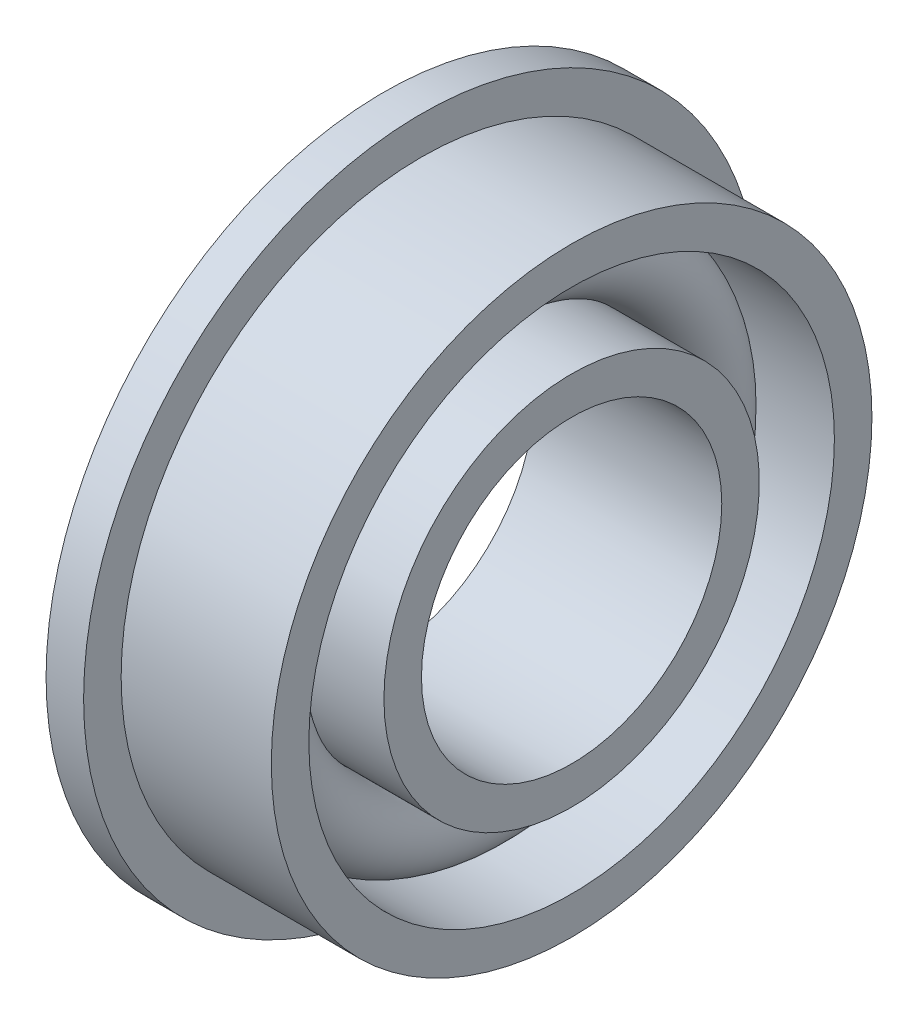
SolidWorks part; units mm, degrees
ref_plane "Front Plane" through (0, 0, 0) normal (0, 0, 1) x (1, 0, 0)
ref_plane "Top Plane" through (0, 0, 0) normal (0, 1, 0) x (1, 0, 0)
ref_plane "Right Plane" through (0, 0, 0) normal (1, 0, 0) x (0, 0, -1)
sketch "Sketch1" plane through (0, 0, 0) normal (0, 0, 1) x (1, 0, 0)
  line L0 (0, 0) -> (5, 0) construction
  line L1 (0, 4) -> (5, 4)
  line L2 (5, 4) -> (5, 5)
  line L3 (5, 5) -> (0, 5)
  line L4 (0, 5) -> (0, 4)
  line L5 (5, 7) -> (0, 7)
  line L6 (0, 7) -> (0, 9)
  line L7 (0, 9) -> (1, 9)
  line L8 (1, 9) -> (1, 8)
  line L9 (1, 8) -> (5, 8)
  line L10 (5, 8) -> (5, 7)
  line L11 (2.5, 0) -> (2.5, 8) construction
  line L12 (5, 4) -> (5, 0) construction
  circle A0 centre (2.5, 6) radius 1
  dimension "D1" = 16
  dimension "D2" = 18
  dimension "D3" = 8
  dimension "D4" = 5
  dimension "D5" = 1
  dimension "D6" = 1
  dimension "D7" = 1
revolve "Revolve1" add sketch "Sketch1" angle 360 about L0
